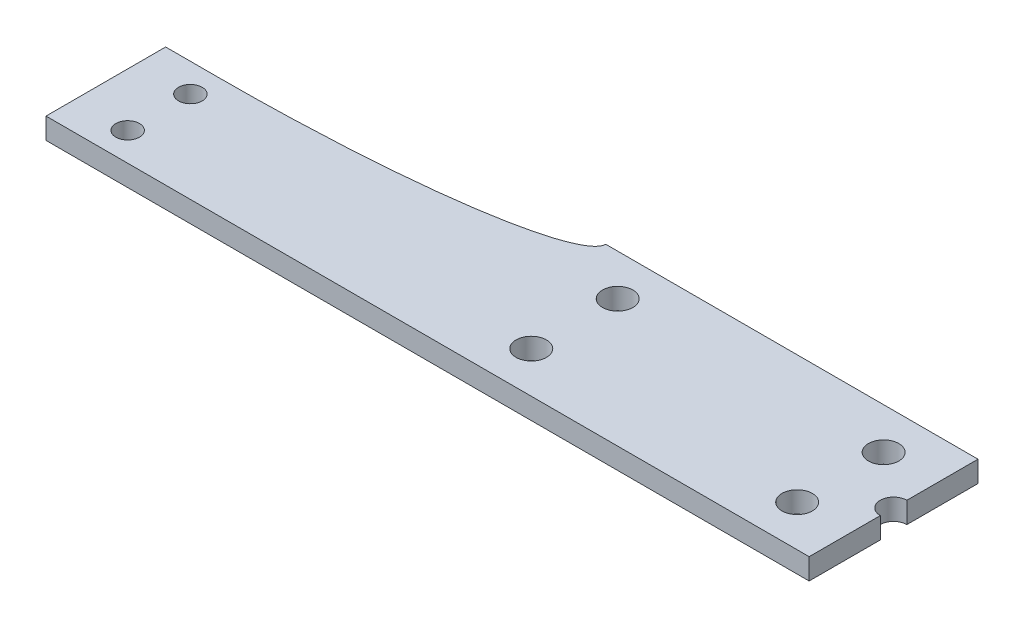
SolidWorks part; units mm, degrees
ref_plane "Front Plane" through (0, 0, 0) normal (0, 0, 1) x (1, 0, 0)
ref_plane "Top Plane" through (0, 0, 0) normal (0, 1, 0) x (1, 0, 0)
ref_plane "Right Plane" through (0, 0, 0) normal (1, 0, 0) x (0, 0, -1)
sketch "Sketch1" plane through (0, 0, 0) normal (0, 1, 0) x (1, 0, 0)
  line L0 (-26.7, -6.35) -> (-26.7, 2.65) construction
  line L1 (-26.7, -6.35) -> (26.7, -6.35)
  line L2 (-26.7, -6.35) -> (-26.7, 6.35) construction
  line L3 (-26.7, 6.35) -> (26.7, 6.35) construction
  line L4 (26.7, -6.35) -> (26.7, 6.35) construction
  line L5 (-26.7, -6.35) -> (26.7, 6.35) construction
  line L6 (-26.7, 6.35) -> (26.7, -6.35) construction
  line L7 (26.7, 6.35) -> (-1.3, 6.35)
  line L8 (-26.7, -6.35) -> (-30.7, -6.35)
  line L9 (-30.7, -6.35) -> (-30.7, 2.65)
  line L10 (-30.7, 2.65) -> (-26.7, 2.65)
  line L11 (-26.7, 0.51) -> (-26.7, 2.65) construction
  line L12 (-26.7, -4.21) -> (-26.7, -6.35) construction
  line L13 (2.7, 6.35) -> (2.7, -6.35) construction
  line L14 (22.7, 6.35) -> (22.7, -6.35) construction
  line L15 (2.7, -3.25) -> (2.7, -6.35) construction
  line L16 (2.7, 3.25) -> (2.7, 6.35) construction
  line L17 (2.7, 3.25) -> (22.7, 3.25) construction
  line L18 (2.7, -3.25) -> (22.7, -3.25) construction
  line L19 (26.7, 1) -> (26.7, 6.35)
  line L20 (26.7, -6.35) -> (26.7, -1)
  circle A0 centre (-26.7, 0.51) radius 0.89
  circle A1 centre (-26.7, -4.21) radius 0.89
  circle A2 centre (2.7, 3.25) radius 1.143
  circle A3 centre (2.7, -3.25) radius 1.143
  circle A4 centre (22.7, 3.25) radius 1.143
  circle A5 centre (22.7, -3.25) radius 1.143
  arc A6 (26.7, 1) -> (26.7, -1) centre (26.7, 0) ccw
  ellipse E0 centre (-26.7, 6.35) end of major axis (-1.3, 6.35) minor radius 3.7 (-26.7, 2.65) -> (-1.3, 6.35) ccw
  point P0 (0, 0)
  dimension "D6" = 1.78
  dimension "D10" = 2.286
  dimension "D12" = 1
  dimension "D1" = 12.7
  dimension "D2" = 53.4
  dimension "D3" = 9
  dimension "D4" = 25.4
  dimension "D5" = 4
  dimension "D7" = 4.72
  dimension "D8" = 4
  dimension "D9" = 20
  dimension "D11" = 6.5
extrude "Boss-Extrude1" add sketch "Sketch1" along normal blind 1.5875
